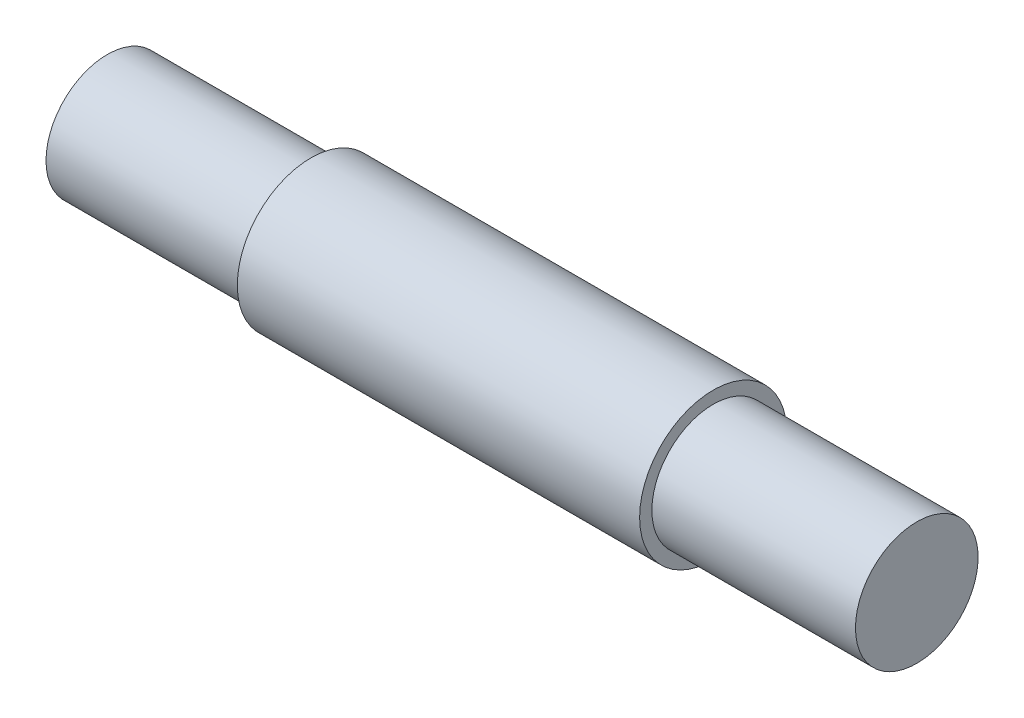
SolidWorks part; units mm, degrees
ref_plane "Front Plane" through (0, 0, 0) normal (0, 0, 1) x (1, 0, 0)
ref_plane "Top Plane" through (0, 0, 0) normal (0, 1, 0) x (1, 0, 0)
ref_plane "Right Plane" through (0, 0, 0) normal (1, 0, 0) x (0, 0, -1)
sketch "Sketch1" plane through (0, 0, 0) normal (0, 1, 0) x (1, 0, 0)
  line L0 (-145.7746, 0) -> (184.2254, 0)
  line L1 (0, 181.338) -> (0, -176.4085) construction
  line L2 (-145.7746, 0) -> (-145.7746, 25)
  line L3 (-145.7746, 25) -> (-62.7746, 25)
  line L4 (-62.7746, 25) -> (-62.7746, 30)
  line L5 (-62.7746, 30) -> (101.2254, 30)
  line L6 (101.2254, 30) -> (101.2254, 25)
  line L7 (101.2254, 25) -> (184.2254, 25)
  line L8 (184.2254, 25) -> (184.2254, 0)
  dimension "D1" = 25
  dimension "D4" = 330
  dimension "D5" = 164
  dimension "D6" = 83
  dimension "D7" = 83
revolve "Revolve2" add sketch "Sketch1" angle 360 about L0
cosmetic thread "Cosmetic Thread1" parameters "D2"=42.516
cosmetic thread "Cosmetic Thread2" parameters "D2"=42.516
